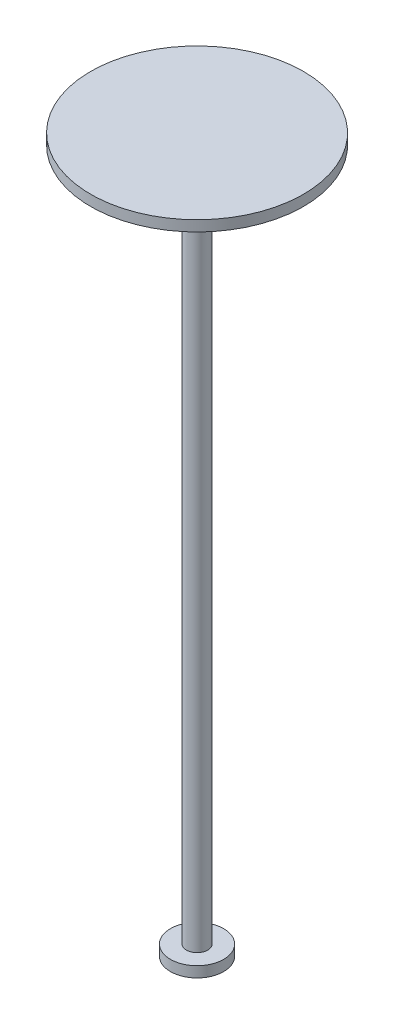
SolidWorks part; units mm, degrees
ref_plane "Front Plane" through (0, 0, 0) normal (0, 0, 1) x (1, 0, 0)
ref_plane "Top Plane" through (0, 0, 0) normal (0, 1, 0) x (1, 0, 0)
ref_plane "Right Plane" through (0, 0, 0) normal (1, 0, 0) x (0, 0, -1)
sketch "Sketch1" plane through (0, 0, 0) normal (0, 0, 1) x (1, 0, 0)
  line L0 (0, 0) -> (0, 165.2468)
  line L1 (0, 165.2468) -> (25.4, 165.2468)
  line L3 (25.4, 165.2468) -> (25.4, 162.7068)
  line L4 (2.54, -2.3932) -> (2.54, 162.7068)
  line L5 (2.54, 162.7068) -> (25.4, 162.7068)
  line L9 (2.54, -2.3932) -> (6.35, -2.3932)
  line L10 (0, 0) -> (0, -4.9332)
  line L11 (0, -4.9332) -> (6.35, -4.9332)
  line L12 (6.35, -2.3932) -> (6.35, -4.9332)
  dimension "D1" = 6.35
  dimension "D2" = 25.4
  dimension "D3" = 2.54
  dimension "D4" = 2.54
  dimension "D5" = 165.1
  dimension "D6" = 2.54
revolve "Revolve1" add sketch "Sketch1" angle 360 about L0
